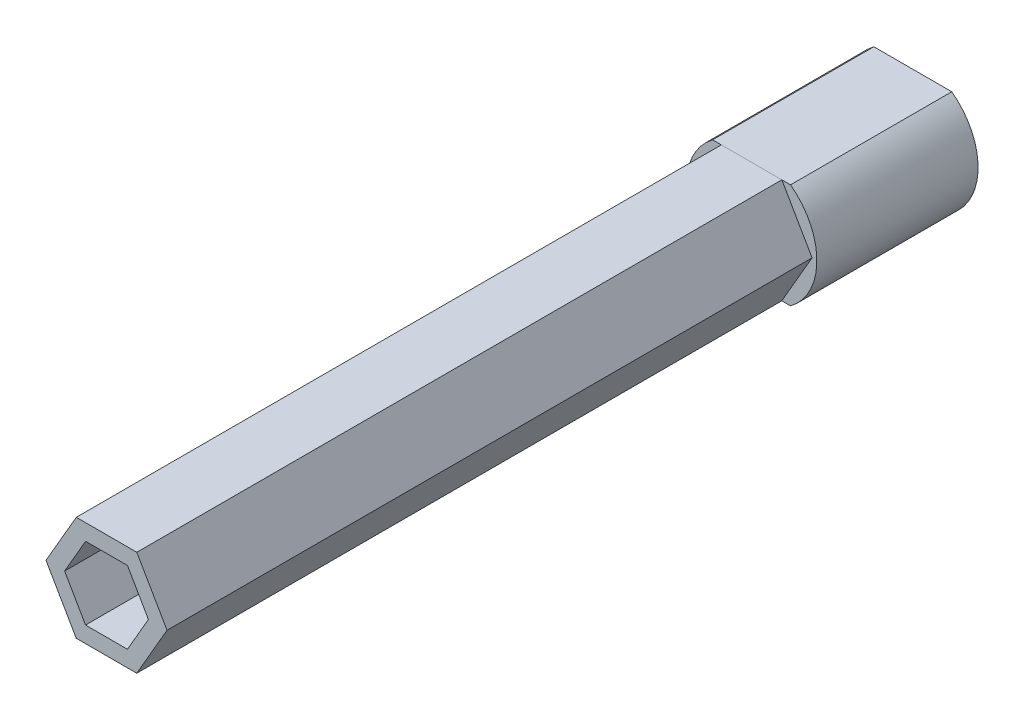
SolidWorks part; units mm, degrees
ref_plane "Front Plane" through (0, 0, 0) normal (0, 0, 1) x (1, 0, 0)
ref_plane "Top Plane" through (0, 0, 0) normal (0, 1, 0) x (1, 0, 0)
ref_plane "Right Plane" through (0, 0, 0) normal (1, 0, 0) x (0, 0, -1)
sketch "Sketch1" plane through (0, 0, 0) normal (0, 0, 1) x (1, 0, 0)
  line L0 (-2.4166, 3.25) -> (2.4166, 3.25)
  line L1 (-2.4166, -3.25) -> (2.4166, -3.25)
  arc A0 (-2.4166, 3.25) -> (-2.4166, -3.25) centre (0, 0) ccw
  arc A2 (2.4166, -3.25) -> (2.4166, 3.25) centre (0, 0) ccw
  dimension "D1" = 8.1
  dimension "D3" = 6.5
extrude "Boss-Extrude2" add sketch "Sketch1" along normal blind 10
sketch "Sketch3" plane through (0, 0, 0) normal (0, 0, -1) x (-1, 0, 0)
  line L2 (2.4166, 3.25) -> (-2.4166, 3.25)
  line L3 (-2.4166, -3.25) -> (2.4166, -3.25)
  line L4 (2.4166, 3.25) -> (-2.4166, 3.25)
  line L5 (-2.4166, -3.25) -> (2.4166, -3.25)
  line L6 (2.4166, 3.25) -> (-2.4166, 3.25)
  line L7 (-2.4166, -3.25) -> (2.4166, -3.25)
  line L8 (1.8547, 1.75) -> (-1.8547, 1.75)
  line L9 (-1.8547, -1.75) -> (1.8547, -1.75)
  arc A2 (2.4166, -3.25) -> (2.4166, 3.25) centre (0, 0) ccw
  arc A3 (-2.4166, 3.25) -> (-2.4166, -3.25) centre (0, 0) ccw
  arc A4 (2.4166, -3.25) -> (2.4166, 3.25) centre (0, 0) ccw
  arc A5 (-2.4166, 3.25) -> (-2.4166, -3.25) centre (0, 0) ccw
  arc A6 (-2.4166, 3.25) -> (-2.4166, -3.25) centre (0, 0) ccw
  arc A7 (2.4166, -3.25) -> (2.4166, 3.25) centre (0, 0) ccw
  arc A8 (1.8547, -1.75) -> (1.8547, 1.75) centre (0, 0) ccw
  arc A9 (-1.8547, 1.75) -> (-1.8547, -1.75) centre (0, 0) ccw
  dimension "D1" = 0
sketch "Sketch4" plane through (0, 0, 10) normal (0, 0, 1) x (1, 0, 0)
  line L1 (1.8744, -3.2511) -> (3.7528, -0.0023)
  line L2 (3.7528, -0.0023) -> (1.8783, 3.2489)
  line L3 (1.8783, 3.2489) -> (-1.8744, 3.2511)
  line L4 (-1.8744, 3.2511) -> (-3.7528, 0.0023)
  line L5 (-3.7528, 0.0023) -> (-1.8783, -3.2489)
  line L6 (-1.8783, -3.2489) -> (1.8744, -3.2511)
  circle A0 centre (0, 0) radius 3.25 construction
  dimension "D1" = 6.5
extrude "Boss-Extrude3" add sketch "Sketch4" along normal blind 40
sketch "Sketch5" plane through (0, 0, 50) normal (0, 0, 1) x (1, 0, 0)
  line L12 (-1.3004, -2.2492) -> (1.2977, -2.2508)
  line L13 (1.2977, -2.2508) -> (2.5981, -0.0016)
  line L14 (2.5981, -0.0016) -> (1.3004, 2.2492)
  line L15 (1.3004, 2.2492) -> (-1.2977, 2.2508)
  line L16 (-1.2977, 2.2508) -> (-2.5981, 0.0016)
  line L17 (-2.5981, 0.0016) -> (-1.3004, -2.2492)
  line L18 (-1.3004, -2.2492) -> (1.2977, -2.2508)
  line L19 (1.2977, -2.2508) -> (2.5981, -0.0016)
  line L20 (2.5981, -0.0016) -> (1.3004, 2.2492)
  line L21 (1.3004, 2.2492) -> (-1.2977, 2.2508)
  line L22 (-1.2977, 2.2508) -> (-2.5981, 0.0016)
  line L23 (-2.5981, 0.0016) -> (-1.3004, -2.2492)
  dimension "D1" = 1
extrude "Cut-Extrude3" cut sketch "Sketch5" against normal blind 40 and the other way through all
extrude "Cut-Extrude4" cut sketch "Sketch3" against normal blind 10 contours A8 L8 A9 L9
